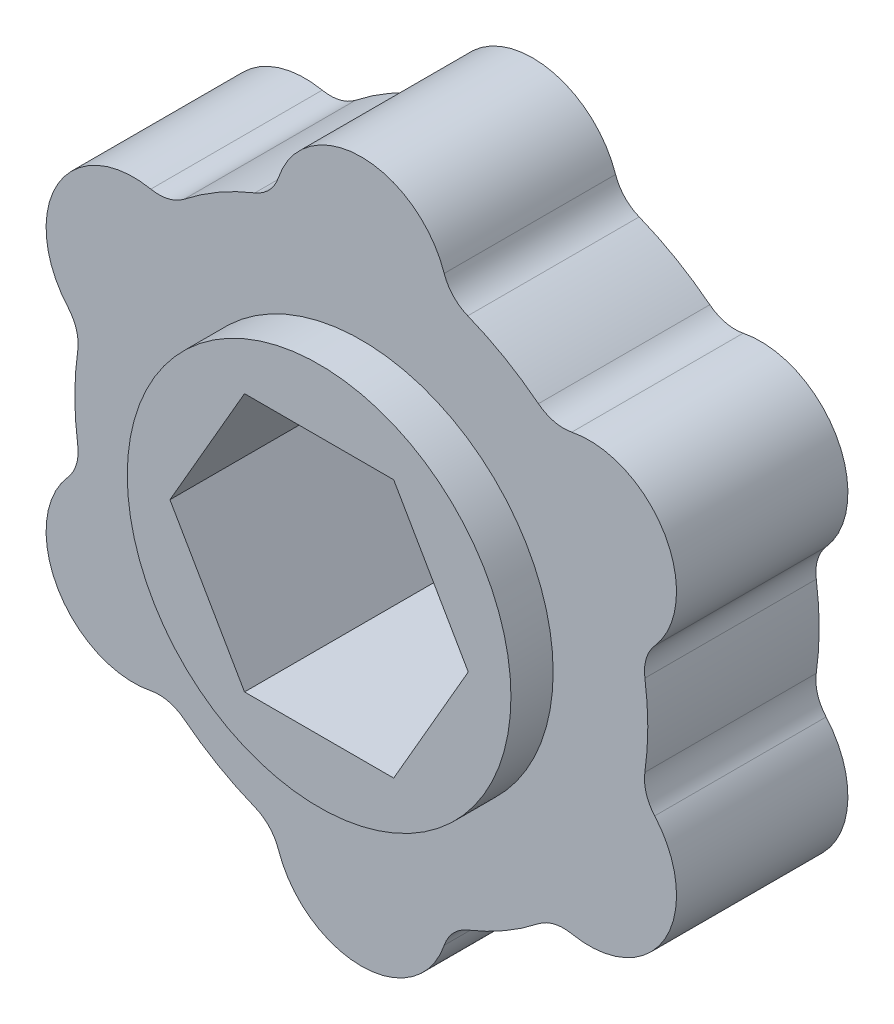
SolidWorks part; units mm, degrees
material "PET"
ref_plane "Front Plane" through (0, 0, 0) normal (0, 0, 1) x (1, 0, 0)
ref_plane "Top Plane" through (0, 0, 0) normal (0, 1, 0) x (1, 0, 0)
ref_plane "Right Plane" through (0, 0, 0) normal (1, 0, 0) x (0, 0, -1)
sketch "Sketch5" plane through (0, 0, 0) normal (0, 0, 1) x (1, 0, 0)
  line L0 (0, 0) -> (0, 13.0556) construction
  circle A0 centre (0, 0) radius 14.224
  circle A1 centre (0, 0) radius 17.399 construction
  arc A2 (-4.3147, 13.5538) -> (4.3147, 13.5538) centre (0, 13.0556) cw
  arc A3 (9.5806, 10.5136) -> (13.8953, 3.0402) centre (11.3065, 6.5278) cw
  arc A4 (13.8953, -3.0402) -> (9.5806, -10.5136) centre (11.3065, -6.5278) cw
  arc A5 (4.3147, -13.5538) -> (-4.3147, -13.5538) centre (0, -13.0556) cw
  arc A6 (-9.5806, -10.5136) -> (-13.8953, -3.0402) centre (-11.3065, -6.5278) cw
  arc A7 (-13.8953, 3.0402) -> (-9.5806, 10.5136) centre (-11.3065, 6.5278) cw
  point P24 (0, 0)
  dimension "D1" = 28.448
  dimension "D2" = 34.798
  dimension "D3" = 4.3434
  dimension "D4" = 6
extrude "Boss-Extrude2" add sketch "Sketch5" along normal blind 8.509 contours A7 A0 | A2 A0 | A3 A0 | A4 A0 | A5 A0 | A6 A0
fillet "Fillet1" radius 2.032 12 edges at (-13.8953, 3.0402, 4.2545) (-9.5806, 10.5136, 4.2545) (-4.3147, 13.5538, 4.2545) (4.3147, 13.5538, 4.2545) (9.5806, 10.5136, 4.2545) (13.8953, 3.0402, 4.2545) (13.8953, -3.0402, 4.2545) (9.5806, -10.5136, 4.2545) (4.3147, -13.5538, 4.2545) (-4.3147, -13.5538, 4.2545) (-9.5806, -10.5136, 4.2545) (-13.8953, -3.0402, 4.2545)
sketch "Sketch6" plane through (0, 0, 8.509) normal (0, 0, 1) x (1, 0, 0)
  line L1 (7.4057, 0) -> (3.7028, 6.4135)
  line L2 (3.7028, 6.4135) -> (-3.7028, 6.4135)
  line L3 (-3.7028, 6.4135) -> (-7.4057, 0)
  line L4 (-7.4057, 0) -> (-3.7028, -6.4135)
  line L5 (-3.7028, -6.4135) -> (3.7028, -6.4135)
  line L6 (3.7028, -6.4135) -> (7.4057, 0)
  circle A0 centre (0, 0) radius 6.4135 construction
  dimension "D1" = 12.827
extrude "Cut-Extrude1" cut sketch "Sketch6" against normal through all
sketch "Sketch7" plane through (0, 0, 0) normal (0, 0, -1) x (-1, 0, 0)
  line L0 (-7.4057, 0) -> (-3.7028, 6.4135) construction
  line L1 (-3.7028, -6.4135) -> (-7.4057, 0) construction
  line L2 (3.7028, -6.4135) -> (-3.7028, -6.4135) construction
  line L3 (7.4057, 0) -> (3.7028, -6.4135) construction
  line L4 (3.7028, 6.4135) -> (7.4057, 0) construction
  line L5 (-3.7028, 6.4135) -> (3.7028, 6.4135) construction
  line L6 (-7.4057, 0) -> (-3.7028, 6.4135)
  line L7 (-3.7028, -6.4135) -> (-7.4057, 0)
  line L8 (3.7028, -6.4135) -> (-3.7028, -6.4135)
  line L9 (7.4057, 0) -> (3.7028, -6.4135)
  line L10 (3.7028, 6.4135) -> (7.4057, 0)
  line L11 (-3.7028, 6.4135) -> (3.7028, 6.4135)
  circle A0 centre (0, 0) radius 9.525
  dimension "D1" = 19.05
extrude "Boss-Extrude3" add sketch "Sketch7" along normal blind 1.0795
sketch "Sketch8" plane through (0, 0, 8.509) normal (0, 0, 1) x (1, 0, 0)
  line L1 (3.7028, -6.4135) -> (7.4057, 0)
  line L2 (7.4057, 0) -> (3.7028, 6.4135)
  line L3 (3.7028, 6.4135) -> (-3.7028, 6.4135)
  line L4 (-3.7028, 6.4135) -> (-7.4057, 0)
  line L5 (-7.4057, 0) -> (-3.7028, -6.4135)
  line L6 (-3.7028, -6.4135) -> (3.7028, -6.4135)
  circle A0 centre (0, 0) radius 9.525
  circle A1 centre (0, 0) radius 6.4135 construction
  dimension "D1" = 19.05
  dimension "D2" = 12.827
extrude "Boss-Extrude4" add sketch "Sketch8" along normal blind 2.0955
equation "\"D1@Boss-Extrude2\"=0.335000in"
equation "\"D1@Boss-Extrude3\"=0.21-(0.335/2)"
equation "\"D1@Boss-Extrude4\"=0.21-(0.335/2)+(1/16)-0.02250"
